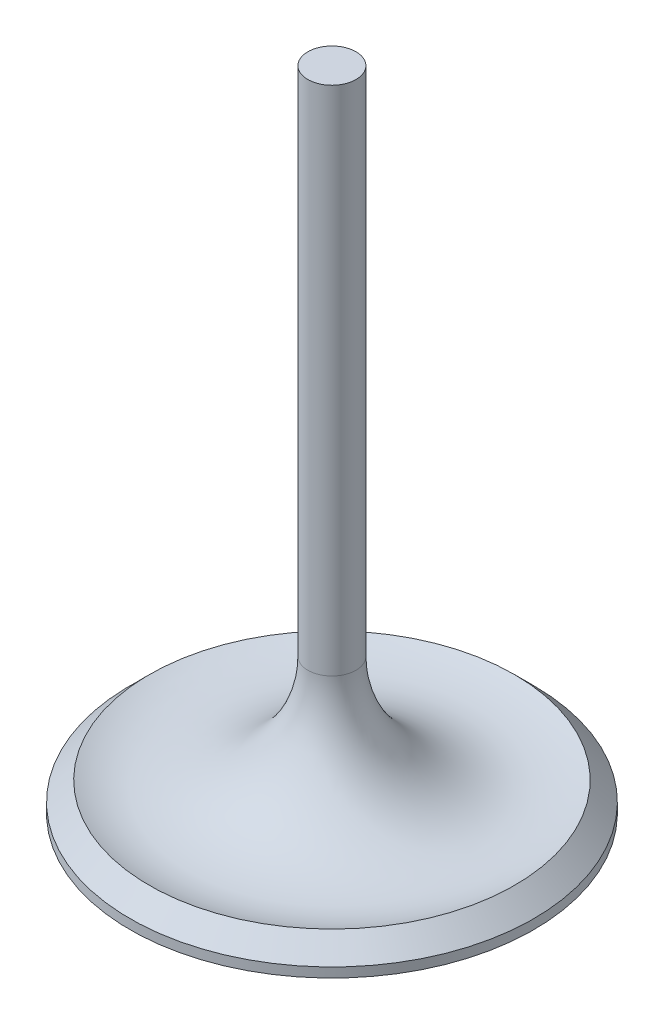
SolidWorks part; units mm, degrees
ref_plane "Front Plane" through (0, 0, 0) normal (0, 0, 1) x (1, 0, 0)
ref_plane "Top Plane" through (0, 0, 0) normal (0, 1, 0) x (1, 0, 0)
ref_plane "Right Plane" through (0, 0, 0) normal (1, 0, 0) x (0, 0, -1)
sketch "Sketch1" plane through (0, 0, 0) normal (0, 0, 1) x (1, 0, 0)
  line L0 (0, 0) -> (0, 85.55)
  line L1 (0, 85.55) -> (3.18, 85.55)
  line L2 (3.18, 85.55) -> (3.18, 17.9547)
  line L3 (0, 0) -> (26.67, 0)
  line L4 (26.67, 0) -> (26.67, 1.27)
  line L5 (26.67, 1.27) -> (24.13, 3.81)
  arc A0 (3.18, 17.9547) -> (24.13, 3.81) centre (18.43, 17.9547) ccw
  dimension "D1" = 3.18
  dimension "D7" = 30.5
  dimension "D2" = 85.55
  dimension "D3" = 26.67
  dimension "D4" = 1.27
  dimension "D5" = 3.81
  dimension "D6" = 45
revolve "Revolve1" add sketch "Sketch1" angle 360 about L0
